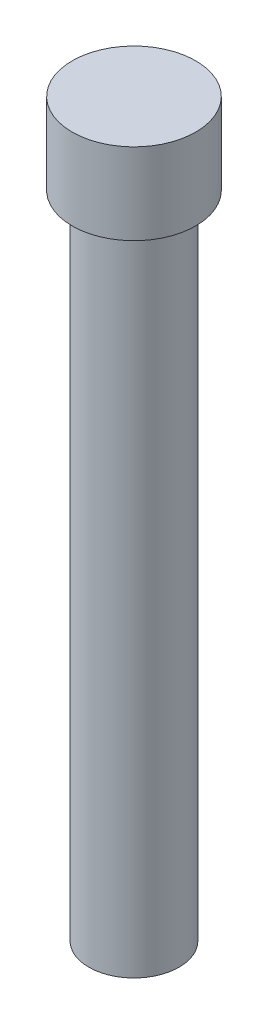
SolidWorks part; units mm, degrees
ref_plane "Front Plane" through (0, 0, 0) normal (0, 0, 1) x (1, 0, 0)
ref_plane "Top Plane" through (0, 0, 0) normal (0, 1, 0) x (1, 0, 0)
ref_plane "Right Plane" through (0, 0, 0) normal (1, 0, 0) x (0, 0, -1)
sketch "Sketch1" plane through (0, 0, 0) normal (0, 1, 0) x (1, 0, 0)
  circle A0 centre (0, 0) radius 1.764
  dimension "D1" = 3.5281
extrude "Boss-Extrude1" add sketch "Sketch1" along normal blind 25.4
sketch "Sketch2" plane through (0, 25.4, 0) normal (0, 1, 0) x (1, 0, 0)
  circle A0 centre (0, 0) radius 2.413
  dimension "D1" = 4.826
extrude "Boss-Extrude2" add sketch "Sketch2" along normal blind 3.175
